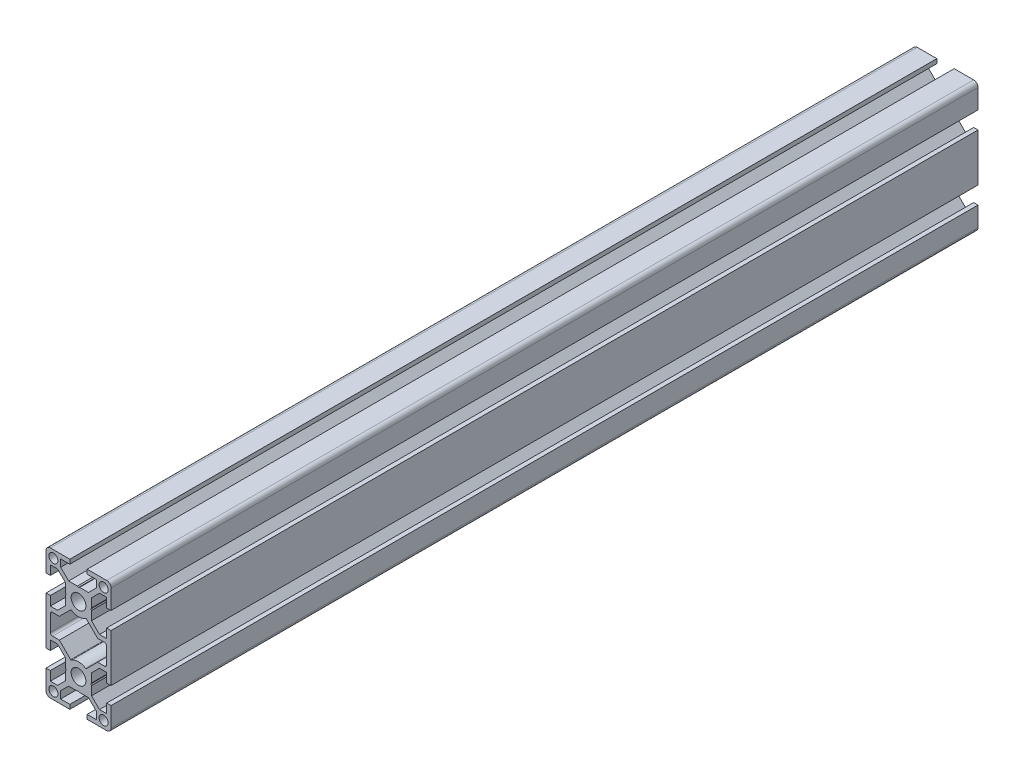
SolidWorks part; units mm, degrees
ref_plane "Front Plane" through (0, 0, 0) normal (0, 0, 1) x (1, 0, 0)
ref_plane "Top Plane" through (0, 0, 0) normal (0, 1, 0) x (1, 0, 0)
ref_plane "Right Plane" through (0, 0, 0) normal (1, 0, 0) x (0, 0, -1)
sketch "Model" plane through (0, 0, 0) normal (0, 0, 1) x (1, 0, 0)
  line L0 (9.395, -26.6) -> (13.805, -26.6) construction
  line L1 (11.6, -28.805) -> (11.6, -24.395) construction
  line L2 (9.395, 26.6) -> (13.805, 26.6) construction
  line L3 (11.6, 24.395) -> (11.6, 28.805) construction
  line L4 (-3.57, 15) -> (3.57, 15) construction
  line L5 (0, 11.43) -> (0, 18.57) construction
  line L6 (-3.57, -15) -> (3.57, -15) construction
  line L7 (0, -18.57) -> (0, -11.43) construction
  line L8 (-13.805, 26.6) -> (-9.395, 26.6) construction
  line L9 (-11.6, 24.395) -> (-11.6, 28.805) construction
  line L10 (-13.805, -26.6) -> (-9.395, -26.6) construction
  line L11 (-11.6, -28.805) -> (-11.6, -24.395) construction
  line L12 (13, -11) -> (15, -11)
  line L13 (-8.8358, 4.75) -> (-12, 4.75)
  line L14 (-3.6518, 9.934) -> (-8.8358, 4.75)
  line L15 (8.8358, 4.75) -> (3.6518, 9.934)
  line L16 (12, 4.75) -> (8.8358, 4.75)
  line L17 (13, -3.75) -> (13, 3.75)
  line L18 (8.8358, -4.75) -> (12, -4.75)
  line L19 (3.6518, -9.934) -> (8.8358, -4.75)
  line L20 (-8.8358, -4.75) -> (-3.6518, -9.934)
  line L21 (-12, -4.75) -> (-8.8358, -4.75)
  line L22 (-13, 3.75) -> (-13, -3.75)
  line L23 (-15, 28) -> (-15, 19)
  line L24 (-15, 19) -> (-13, 19)
  line L25 (-13, 19) -> (-13, 23.25)
  line L26 (-13, 23.25) -> (-9.6642, 23.25)
  line L27 (-9.6642, 23.25) -> (-6, 19.5858)
  line L28 (-6, 19.5858) -> (-6, 15.5196)
  line L29 (-6, 15.5196) -> (-5.7, 15)
  line L30 (-5.7, 15) -> (-6, 14.4804)
  line L31 (-6, 14.4804) -> (-6, 10.4142)
  line L32 (-6, 10.4142) -> (-9.6642, 6.75)
  line L33 (-9.6642, 6.75) -> (-13, 6.75)
  line L34 (-13, 6.75) -> (-13, 11)
  line L35 (-13, 11) -> (-15, 11)
  line L36 (-15, 11) -> (-15, -11)
  line L37 (-15, -11) -> (-13, -11)
  line L38 (-13, -11) -> (-13, -6.75)
  line L39 (-13, -6.75) -> (-9.6642, -6.75)
  line L40 (-9.6642, -6.75) -> (-6, -10.4142)
  line L41 (-6, -10.4142) -> (-6, -14.4804)
  line L42 (-6, -14.4804) -> (-5.7, -15)
  line L43 (-5.7, -15) -> (-6, -15.5196)
  line L44 (-6, -15.5196) -> (-6, -19.5858)
  line L45 (-6, -19.5858) -> (-9.6642, -23.25)
  line L46 (-9.6642, -23.25) -> (-13, -23.25)
  line L47 (-13, -23.25) -> (-13, -19)
  line L48 (-13, -19) -> (-15, -19)
  line L49 (-15, -19) -> (-15, -28)
  line L50 (-13, -30) -> (-4, -30)
  line L51 (-4, -30) -> (-4, -28)
  line L52 (-4, -28) -> (-8.25, -28)
  line L53 (-8.25, -28) -> (-8.25, -24.6642)
  line L54 (-8.25, -24.6642) -> (-4.5858, -21)
  line L55 (-4.5858, -21) -> (-0.5196, -21)
  line L56 (-0.5196, -21) -> (0, -20.7)
  line L57 (0, -20.7) -> (0.5196, -21)
  line L58 (0.5196, -21) -> (4.5858, -21)
  line L59 (4.5858, -21) -> (8.25, -24.6642)
  line L60 (8.25, -24.6642) -> (8.25, -28)
  line L61 (8.25, -28) -> (4, -28)
  line L62 (4, -28) -> (4, -30)
  line L63 (4, -30) -> (13, -30)
  line L64 (15, -28) -> (15, -19)
  line L65 (15, -19) -> (13, -19)
  line L66 (13, -19) -> (13, -23.25)
  line L67 (13, -23.25) -> (9.6642, -23.25)
  line L68 (9.6642, -23.25) -> (6, -19.5858)
  line L69 (6, -19.5858) -> (6, -15.5196)
  line L70 (6, -15.5196) -> (5.7, -15)
  line L71 (5.7, -15) -> (6, -14.4804)
  line L72 (6, -14.4804) -> (6, -10.4142)
  line L73 (6, -10.4142) -> (9.6642, -6.75)
  line L74 (9.6642, -6.75) -> (13, -6.75)
  line L75 (13, -6.75) -> (13, -11)
  line L76 (15, -11) -> (15, 11)
  line L77 (15, 11) -> (13, 11)
  line L78 (13, 11) -> (13, 6.75)
  line L79 (13, 6.75) -> (9.6642, 6.75)
  line L80 (9.6642, 6.75) -> (6, 10.4142)
  line L81 (6, 10.4142) -> (6, 14.4804)
  line L82 (6, 14.4804) -> (5.7, 15)
  line L83 (5.7, 15) -> (6, 15.5196)
  line L84 (6, 15.5196) -> (6, 19.5858)
  line L85 (6, 19.5858) -> (9.6642, 23.25)
  line L86 (9.6642, 23.25) -> (13, 23.25)
  line L87 (13, 23.25) -> (13, 19)
  line L88 (13, 19) -> (15, 19)
  line L89 (15, 19) -> (15, 28)
  line L90 (13, 30) -> (4, 30)
  line L91 (4, 30) -> (4, 28)
  line L92 (4, 28) -> (8.25, 28)
  line L93 (8.25, 28) -> (8.25, 24.6642)
  line L94 (8.25, 24.6642) -> (4.5858, 21)
  line L95 (4.5858, 21) -> (0.5196, 21)
  line L96 (0.5196, 21) -> (0, 20.7)
  line L97 (0, 20.7) -> (-0.5196, 21)
  line L98 (-0.5196, 21) -> (-4.5858, 21)
  line L99 (-4.5858, 21) -> (-8.25, 24.6642)
  line L100 (-8.25, 24.6642) -> (-8.25, 28)
  line L101 (-8.25, 28) -> (-4, 28)
  line L102 (-4, 28) -> (-4, 30)
  line L103 (-4, 30) -> (-13, 30)
  circle A0 centre (11.6, -26.6) radius 2.1
  circle A1 centre (11.6, 26.6) radius 2.1
  circle A2 centre (0, 15) radius 3.4
  arc A3 (-12, 4.75) -> (-13, 3.75) centre (-12, 3.75) ccw
  arc A4 (-3.2759, 9.9732) -> (-3.6518, 9.934) centre (-3.4397, 9.7219) ccw
  arc A5 (-3.2759, 9.9732) -> (3.2759, 9.9732) centre (0, 15) ccw
  arc A6 (3.6518, 9.934) -> (3.2759, 9.9732) centre (3.4397, 9.7219) ccw
  arc A7 (13, 3.75) -> (12, 4.75) centre (12, 3.75) ccw
  arc A8 (12, -4.75) -> (13, -3.75) centre (12, -3.75) ccw
  arc A9 (3.2759, -9.9732) -> (3.6518, -9.934) centre (3.4397, -9.7219) ccw
  arc A10 (3.2759, -9.9732) -> (-3.2759, -9.9732) centre (0, -15) ccw
  arc A11 (-3.6518, -9.934) -> (-3.2759, -9.9732) centre (-3.4397, -9.7219) ccw
  arc A12 (-13, -3.75) -> (-12, -4.75) centre (-12, -3.75) ccw
  arc A13 (-15, -28) -> (-13, -30) centre (-13, -28) ccw
  arc A14 (13, -30) -> (15, -28) centre (13, -28) ccw
  arc A15 (15, 28) -> (13, 30) centre (13, 28) ccw
  arc A16 (-13, 30) -> (-15, 28) centre (-13, 28) ccw
  circle A17 centre (0, -15) radius 3.4
  circle A18 centre (-11.6, 26.6) radius 2.1
  circle A19 centre (-11.6, -26.6) radius 2.1
extrude "Boss-Extrude1" add sketch "Model" along normal blind 400
